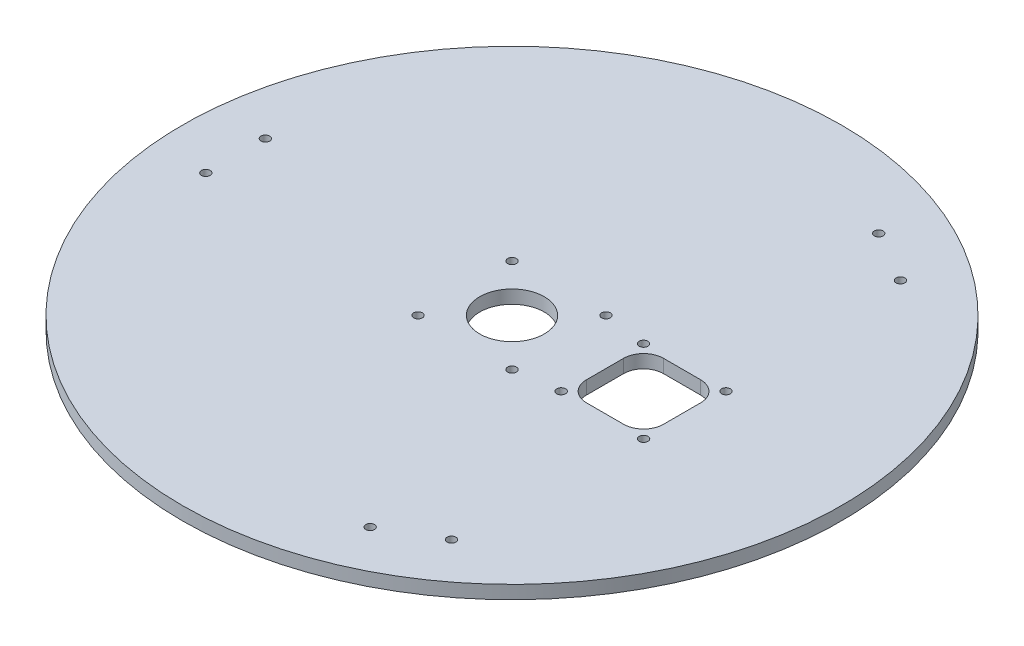
SolidWorks part; units mm, degrees
ref_plane "Alzado" through (0, 0, 0) normal (0, 0, 1) x (1, 0, 0)
ref_plane "Planta" through (0, 0, 0) normal (0, 1, 0) x (1, 0, 0)
ref_plane "Vista lateral" through (0, 0, 0) normal (1, 0, 0) x (0, 0, -1)
sketch "Laser holes" plane through (0, 0, 0) normal (0, 1, 0) x (1, 0, 0)
  line L0 (0, 0) -> (15.5, 0) construction
  line L1 (0, 0) -> (0, 15.5) construction
  line L5 (0, 15.5) -> (15.5, 15.5) construction
  line L6 (15.5, 0) -> (15.5, 15.5) construction
  line L8 (14.5, -7) -> (14.5, 7)
  line L9 (-7, 14.5) -> (7, 14.5)
  line L10 (14.5, 0) -> (14.5, 14.5) construction
  line L11 (0, 14.5) -> (14.5, 14.5) construction
  line L12 (-49.5, 0) -> (-31.8223, 17.6777) construction
  line L13 (-49.5, 0) -> (-153.5, 0) construction
  line L15 (-14.5, -7) -> (-14.5, 7)
  line L16 (-7, -14.5) -> (7, -14.5)
  line L18 (-31.8223, 17.6777) -> (-67.1777, 17.6777) construction
  line L23 (-31.8223, 17.6777) -> (-31.8223, -17.6777) construction
  line L24 (-31.8223, -17.6777) -> (-67.1777, -17.6777) construction
  line L25 (-67.1777, 17.6777) -> (-67.1777, -17.6777) construction
  line L26 (-49.5, 0) -> (2.5, 90.0666) construction
  line L27 (-144.5, 11.2) -> (-162.5, 11.2) construction
  line L28 (-144.5, 11.2) -> (-144.5, -11.2) construction
  line L29 (-144.5, -11.2) -> (-162.5, -11.2) construction
  line L30 (-162.5, 11.2) -> (-162.5, -11.2) construction
  line L31 (-49.5, 0) -> (2.5, -90.0666) construction
  circle A0 centre (15.5, 15.5) radius 1.65
  arc A1 (14.5, 7) -> (7, 14.5) centre (7, 7) ccw
  circle A3 centre (-15.5, 15.5) radius 1.65
  arc A5 (-14.5, 7) -> (-7, 14.5) centre (-7, 7) cw
  arc A6 (-14.5, -7) -> (-7, -14.5) centre (-7, -7) ccw
  circle A8 centre (-15.5, -15.5) radius 1.65
  arc A10 (14.5, -7) -> (7, -14.5) centre (7, -7) cw
  circle A11 centre (15.5, -15.5) radius 1.65
  circle A12 centre (0, 0) radius 25 construction
  circle A13 centre (-49.5, 0) radius 74.5 construction
  circle A14 centre (-49.5, 0) radius 25 construction
  circle A15 centre (-31.8223, 17.6777) radius 1.65
  circle A16 centre (-67.1777, 17.6777) radius 1.65
  circle A17 centre (-67.1777, -17.6777) radius 1.65
  circle A18 centre (-31.8223, -17.6777) radius 1.65
  circle A19 centre (-49.5, 0) radius 12.15
  circle A20 centre (-49.5, 0) radius 124
  circle A27 centre (-153.5, 11.2) radius 1.65
  circle A28 centre (-153.5, -11.2) radius 1.65
  circle A29 centre (-7.1995, 95.6666) radius 1.65
  circle A30 centre (12.1995, 84.4666) radius 1.65
  circle A31 centre (12.1995, -84.4666) radius 1.65
  circle A32 centre (-7.1995, -95.6666) radius 1.65
  point P44 (-14.5, 0)
  point P46 (-49.5, 0)
  point P51 (-153.5, 12.1146)
  point P52 (197.0647, 0)
  point P53 (-144.5, 0)
  point P59 (-153.5, 11.2)
  point P72 (-49.5, 0)
  dimension "D5" = 7.5
  dimension "D2" = 3.3
  dimension "D4" = 50
  dimension "D6" = 149
  dimension "D7" = 50
  dimension "D9" = 3.3
  dimension "D12" = 248
  dimension "D11" = 24.3
  dimension "D16" = 3.3
  dimension "D1" = 15.5
  dimension "D8" = 45
  dimension "D13" = 22.4
  dimension "D14" = 104
  dimension "D15" = 18
  dimension "D3" = 1
  dimension "D10" = 4
  dimension "D17" = 3
extrude "Boss-Extrude4" add sketch "Laser holes" along normal blind 5
equation "\"D1@Laser holes\" = 31 / 2"
equation "\"D14@Laser holes\"=180/2 + 14"
equation "\"D12@Laser holes\"=220+28"
